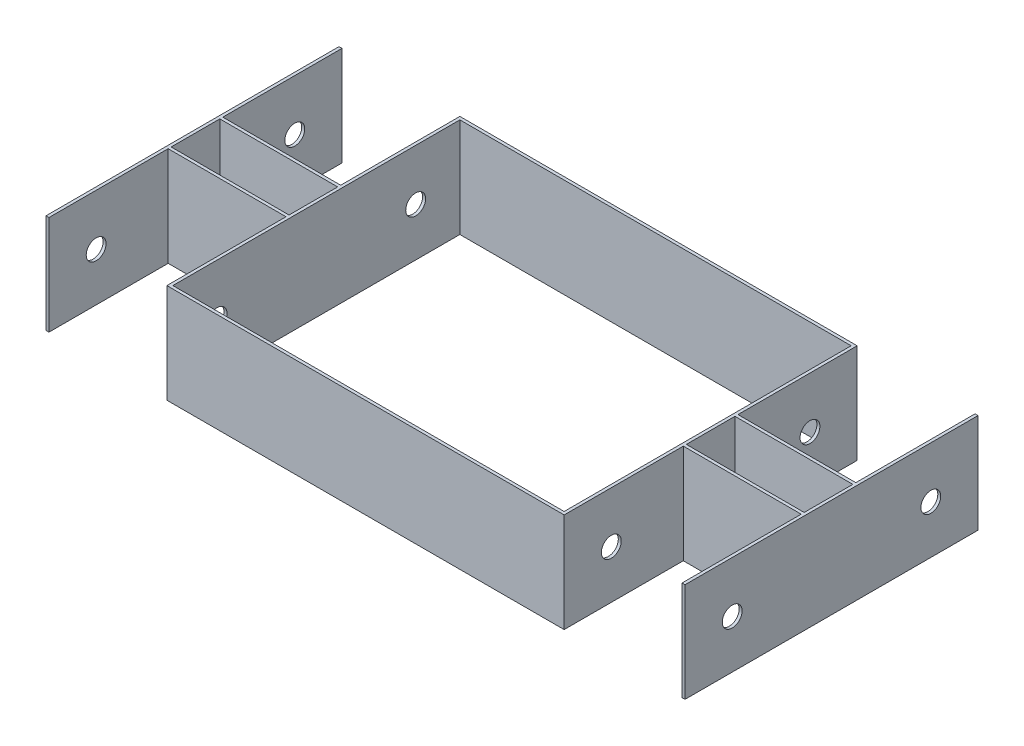
SolidWorks part; units mm, degrees
ref_plane "Front Plane" through (0, 0, 0) normal (0, 0, 1) x (1, 0, 0)
ref_plane "Top Plane" through (0, 0, 0) normal (0, 1, 0) x (1, 0, 0)
ref_plane "Right Plane" through (0, 0, 0) normal (1, 0, 0) x (0, 0, -1)
sketch "Sketch1" plane through (0, 0, 0) normal (0, 1, 0) x (1, 0, 0)
  line L0 (-200, 147.5) -> (200, 147.5)
  line L1 (-197, -144.5) -> (197, -144.5)
  line L2 (-197, -144.5) -> (-197, 144.5)
  line L3 (-197, 144.5) -> (197, 144.5)
  line L4 (197, -144.5) -> (197, 144.5)
  line L5 (-197, -144.5) -> (197, 144.5) construction
  line L6 (-197, 144.5) -> (197, -144.5) construction
  line L7 (200, -147.5) -> (200, 147.5)
  line L8 (-200, -147.5) -> (200, -147.5)
  line L9 (-200, -147.5) -> (-200, 147.5)
  line L10 (200, -24.5) -> (318.7, -24.5)
  line L11 (318.7, -147.5) -> (321.7, -147.5)
  line L12 (318.7, -147.5) -> (318.7, 147.5)
  line L13 (318.7, 147.5) -> (321.7, 147.5)
  line L14 (321.7, -147.5) -> (321.7, 147.5)
  line L15 (200, -27.5) -> (318.7, -27.5)
  line L16 (0, 0) -> (197, 0) construction
  line L17 (200, 27.5) -> (318.7, 27.5)
  line L18 (200, 24.5) -> (318.7, 24.5)
  line L19 (0, 0) -> (0, 144.5) construction
  line L20 (-200, 24.5) -> (-318.7, 24.5)
  line L21 (-200, 27.5) -> (-318.7, 27.5)
  line L22 (-200, -27.5) -> (-318.7, -27.5)
  line L23 (-321.7, -147.5) -> (-321.7, 147.5)
  line L24 (-318.7, 147.5) -> (-321.7, 147.5)
  line L25 (-318.7, -147.5) -> (-318.7, 147.5)
  line L26 (-318.7, -147.5) -> (-321.7, -147.5)
  line L27 (-200, -24.5) -> (-318.7, -24.5)
  line L28 (200, -100) -> (318.7, -100) construction
  line L29 (200, 100) -> (318.7, 100) construction
  point P0 (0, 0)
  dimension "D2" = 3
  dimension "D3" = 118.7
  dimension "D4" = 3
  dimension "D5" = 200
  dimension "D6" = 47.5
  dimension "D7" = 400
  dimension "D8" = 55
  dimension "D1" = 3
extrude "Boss-Extrude1" add sketch "Sketch1" along normal blind 100 contours L1 L4 L3 L2 | L7 L15 L12 L10 | L7 L18 L12 L17 | L25 L20 L9 L21 | L9 L27 L25 L22 | L26 L25 L24 L23
sketch "Sketch3" plane through (321.7, 0, 0) normal (1, 0, 0) x (0, 0, -1)
  line L0 (-147.5, 0) -> (147.5, 0) construction
  line L2 (0, 0) -> (0, 100) construction
  line L3 (-147.5, 100) -> (147.5, 100) construction
  circle A0 centre (-100, 48.5) radius 10
  circle A1 centre (100, 48.5) radius 10
  point P4 (-100, 0)
  point P5 (0, 0)
  dimension "D2" = 20
  dimension "D1" = 48.5
extrude "Cut-Extrude1" cut sketch "Sketch3" against normal through all both and the other way through all
